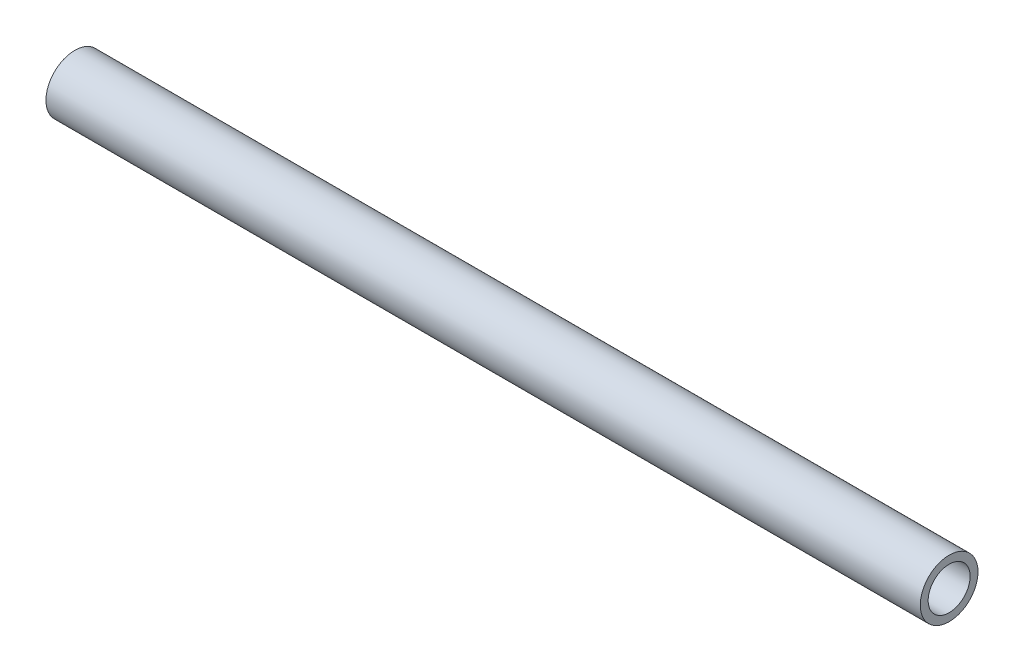
SolidWorks part; units mm, degrees
ref_plane "Front Plane" through (0, 0, 0) normal (0, 0, 1) x (1, 0, 0)
ref_plane "Top Plane" through (0, 0, 0) normal (0, 1, 0) x (1, 0, 0)
ref_plane "Right Plane" through (0, 0, 0) normal (1, 0, 0) x (0, 0, -1)
sketch "Sketch1" plane through (0, 0, 0) normal (1, 0, 0) x (0, 0, -1)
  circle A0 centre (0, 0) radius 4.125
  circle A1 centre (0, 0) radius 3
  dimension "D1" = 8.25
  dimension "D2" = 6
extrude "Boss-Extrude1" add sketch "Sketch1" along normal blind 125
